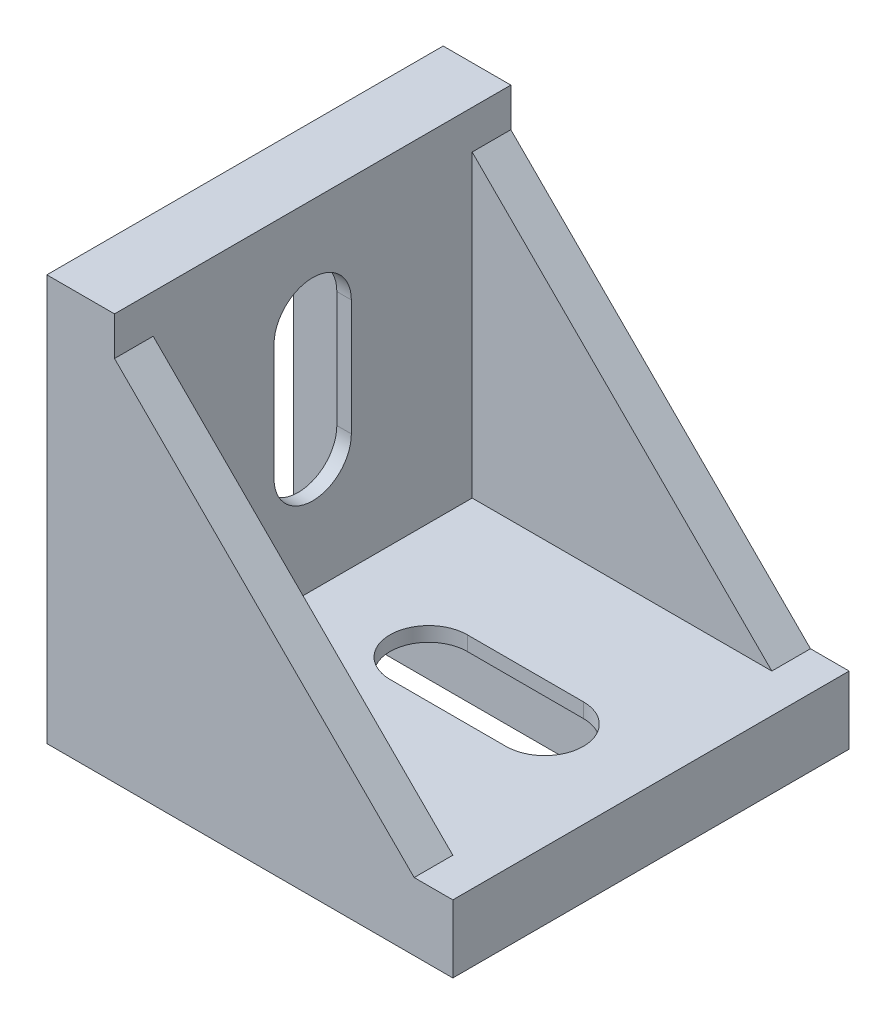
SolidWorks part; units mm, degrees
material "6061 Legierung"
ref_plane "Ebene vorne" through (0, 0, 0) normal (0, 0, 1) x (1, 0, 0)
ref_plane "Ebene oben" through (0, 0, 0) normal (0, 1, 0) x (1, 0, 0)
ref_plane "Ebene rechts" through (0, 0, 0) normal (1, 0, 0) x (0, 0, -1)
sketch "Skizze1" plane through (0, 0, 0) normal (0, 0, 1) x (1, 0, 0)
  line L0 (0, 0) -> (42, 0)
  line L1 (42, 0) -> (42, 7)
  line L2 (42, 7) -> (38, 7)
  line L3 (38, 7) -> (7, 38)
  line L4 (7, 38) -> (7, 42)
  line L5 (7, 42) -> (0, 42)
  line L6 (0, 42) -> (0, 0)
  dimension "D1" = 42
  dimension "D2" = 42
  dimension "D3" = 4
  dimension "D4" = 7
  dimension "D5" = 7
  dimension "D6" = 4
extrude "Aufsatz-Linear austragen1" add sketch "Skizze1" along normal mid plane 41
sketch "Skizze2" plane through (42, 0, 0) normal (1, 0, 0) x (0, 0, -1)
  line L0 (0, 0) -> (0, 44.9281) construction
  line L1 (-20.5, 7) -> (20.5, 7) construction
  line L2 (-16.5, 7) -> (16.5, 7)
  line L3 (-16.5, 7) -> (-16.5, 38)
  line L4 (-16.5, 38) -> (16.5, 38)
  line L5 (16.5, 7) -> (16.5, 38)
  line L6 (-20.5, 38) -> (20.5, 38) construction
  line L7 (20.5, 7) -> (20.5, 38) construction
  dimension "D1" = 4
extrude "Schnitt-Linear austragen1" cut sketch "Skizze2" against normal up to surface (35 mm away) up to face at (7, 40, 0)
sketch "Skizze3" plane through (7, 0, 0) normal (1, 0, 0) x (0, 0, -1)
  line L0 (0, 0) -> (0, 45.4134) construction
  line L1 (0, 19) -> (0, 31) construction
  line L2 (-4, 19) -> (-4, 31)
  line L3 (4, 19) -> (4, 31)
  line L4 (-20.5, 42) -> (20.5, 42) construction
  arc A0 (-4, 19) -> (4, 19) centre (0, 19) ccw
  arc A1 (4, 31) -> (-4, 31) centre (0, 31) ccw
  point P5 (0, 25)
  point P14 (0, 35)
  point P17 (0, 15)
  point P18 (0, 0)
  dimension "D1" = 8
  dimension "D2" = 12
  dimension "D3" = 7
  dimension "D4" = 20
extrude "Schnitt-Linear austragen2" cut sketch "Skizze3" against normal blind 10
sketch "Skizze4" plane through (0, 7, 0) normal (0, 1, 0) x (1, 0, 0)
  line L0 (0, 0) -> (46.8407, 0) construction
  line L1 (19, 0) -> (31, 0) construction
  line L2 (19, 4) -> (31, 4)
  line L3 (19, -4) -> (31, -4)
  line L4 (42, -20.5) -> (42, 20.5) construction
  arc A0 (19, 4) -> (19, -4) centre (19, 0) ccw
  arc A1 (31, -4) -> (31, 4) centre (31, 0) ccw
  point P5 (25, 0)
  point P10 (15, 0)
  point P11 (35, 0)
  dimension "D1" = 12
  dimension "D2" = 8
  dimension "D3" = 7
  dimension "D4" = 20
extrude "Schnitt-Linear austragen3" cut sketch "Skizze4" against normal blind 10
sketch "Skizze5" plane through (0, 0, 0) normal (-1, 0, 0) x (0, 0, 1)
  line L0 (0, 0) -> (0, 43.2652) construction
  line L1 (20.5, 42) -> (20.5, 0) construction
  line L2 (8, 39) -> (17.5, 39)
  line L3 (8, 39) -> (8, 3)
  line L4 (8, 3) -> (17.5, 3)
  line L5 (17.5, 39) -> (17.5, 3)
  line L6 (-5, 36) -> (5, 36)
  line L7 (-5, 36) -> (-5, 8)
  line L8 (-5, 8) -> (5, 8)
  line L9 (5, 36) -> (5, 8)
  line L10 (20.5, 42) -> (-20.5, 42) construction
  line L11 (20.5, 0) -> (-20.5, 0) construction
  line L12 (-8, 39) -> (-17.5, 39)
  line L13 (-8, 39) -> (-8, 3)
  line L14 (-8, 3) -> (-17.5, 3)
  line L15 (-17.5, 39) -> (-17.5, 3)
  dimension "D1" = 10
  dimension "D2" = 3
  dimension "D3" = 3
  dimension "D4" = 3
  dimension "D5" = 3
  dimension "D6" = 6
  dimension "D7" = 8
extrude "Schnitt-Linear austragen4" cut sketch "Skizze5" against normal blind 5.5
sketch "Skizze6" plane through (0, 0, 0) normal (0, -1, 0) x (1, 0, 0)
  line L0 (0, 0) -> (46.4111, 0) construction
  line L1 (42, 20.5) -> (42, -20.5) construction
  line L2 (8, 5) -> (36, 5)
  line L3 (8, 5) -> (8, -5)
  line L4 (8, -5) -> (36, -5)
  line L5 (36, 5) -> (36, -5)
  line L6 (3, 17.5) -> (39, 17.5)
  line L7 (3, 17.5) -> (3, 8)
  line L8 (3, 8) -> (39, 8)
  line L9 (39, 17.5) -> (39, 8)
  line L10 (0, 20.5) -> (42, 20.5) construction
  line L11 (0, 20.5) -> (0, -20.5) construction
  line L12 (3, -17.5) -> (3, -8)
  line L13 (3, -8) -> (39, -8)
  line L14 (39, -17.5) -> (39, -8)
  line L15 (3, -17.5) -> (39, -17.5)
  dimension "D1" = 6
  dimension "D2" = 3
  dimension "D3" = 3
  dimension "D4" = 3
  dimension "D5" = 3
  dimension "D6" = 10
  dimension "D7" = 8
extrude "Schnitt-Linear austragen5" cut sketch "Skizze6" against normal blind 5.5
sketch "Skizze7" plane through (0, 0, 8) normal (0, 0, 1) x (1, 0, 0)
  line L6 (3, 0.5) -> (8, 5.5)
  line L7 (3, 3) -> (3, 0) construction
  line L8 (5.5, 5.5) -> (39, 5.5) construction
  line L9 (8, 5.5) -> (5.5, 5.5)
  line L10 (5.5, 5.5) -> (5.5, 8)
  line L11 (5.5, 8) -> (0.5, 3)
  line L12 (0.5, 3) -> (3, 3)
  line L13 (3, 3) -> (3, 0.5)
  line L14 (3, 3) -> (0, 3) construction
  line L15 (5.5, 39) -> (5.5, 5.5) construction
  point P5 (2.3789, 3)
  point P17 (0, 0)
  dimension "D1" = 2.5
  dimension "D2" = 2.5
  dimension "D3" = 135
  dimension "D4" = 135
extrude "Aufsatz-Linear austragen2" add sketch "Skizze7" along normal up to surface (9.5 mm away) up to face at (11.875, 11.875, 17.5)
sketch "Skizze8" plane through (0, 0, -17.5) normal (0, 0, 1) x (1, 0, 0)
  line L0 (3, 0.5) -> (8, 5.5)
  line L1 (3, 3) -> (3, 0) construction
  line L2 (5.5, 5.5) -> (39, 5.5) construction
  line L3 (8, 5.5) -> (5.5, 5.5)
  line L4 (5.5, 5.5) -> (5.5, 8)
  line L5 (5.5, 39) -> (5.5, 5.5) construction
  line L6 (5.5, 8) -> (0.5, 3)
  line L7 (3, 3) -> (0, 3) construction
  line L8 (0.5, 3) -> (3, 3)
  line L9 (3, 3) -> (3, 0.5)
  dimension "D1" = 2.5
  dimension "D2" = 2.5
  dimension "D3" = 135
  dimension "D4" = 135
extrude "Aufsatz-Linear austragen3" add sketch "Skizze8" along normal up to surface (9.5 mm away) up to face at (11.875, 11.875, -8)
